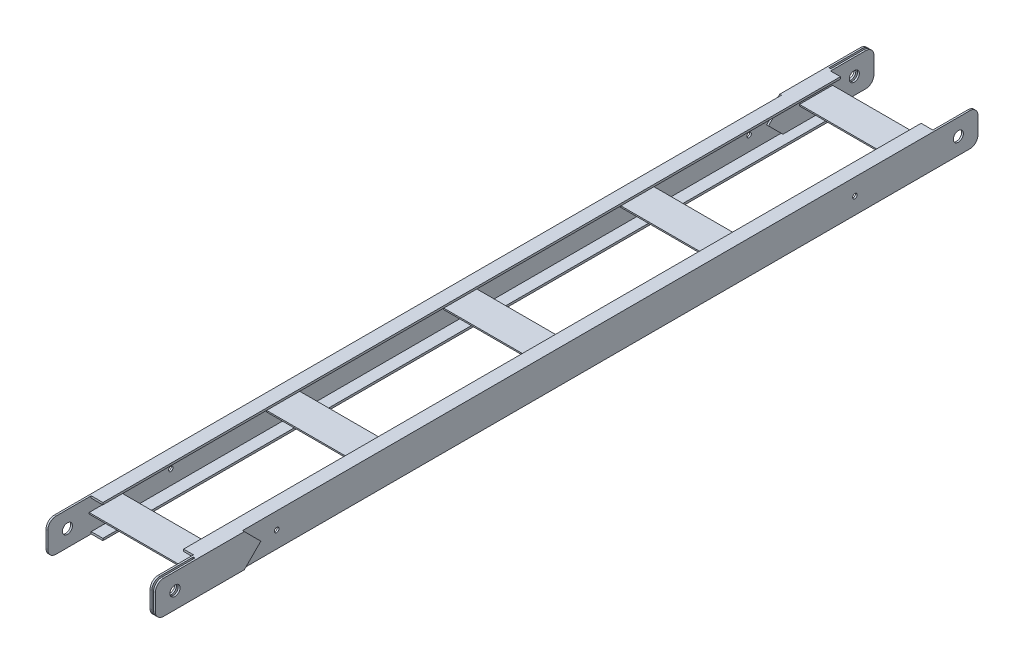
SolidWorks part; units mm, degrees
ref_plane "前视基准面" through (0, 0, 0) normal (0, 0, 1) x (1, 0, 0)
ref_plane "上视基准面" through (0, 0, 0) normal (0, 1, 0) x (1, 0, 0)
ref_plane "右视基准面" through (0, 0, 0) normal (1, 0, 0) x (0, 0, -1)
sketch "草图2" plane through (0, 0, 0) normal (0, 0, 1) x (1, 0, 0)
  line L0 (0, 0) -> (0, 160)
  line L1 (0, 160) -> (65, 160)
  line L2 (65, 160) -> (65, 150)
  line L3 (65, 150) -> (8.5, 150)
  line L4 (8.5, 150) -> (8.5, 10)
  line L5 (8.5, 10) -> (65, 10)
  line L6 (65, 10) -> (65, 0)
  line L7 (65, 0) -> (0, 0)
  line L8 (455, 160) -> (520, 160)
  line L9 (520, 160) -> (520, 0)
  line L10 (520, 0) -> (455, 0)
  line L11 (455, 0) -> (455, 10)
  line L12 (455, 10) -> (511.5, 10)
  line L13 (511.5, 10) -> (511.5, 150)
  line L14 (511.5, 150) -> (455, 150)
  line L15 (455, 150) -> (455, 160)
  dimension "D1" = 160
  dimension "D2" = 10
  dimension "D3" = 8.5
  dimension "D4" = 65
  dimension "D5" = 520
extrude "拉伸1" add sketch "草图2" along normal blind 3985
sketch "草图5" plane through (0, 0, 0) normal (-1, 0, 0) x (0, 0, 1)
  line L0 (200, 95) -> (360, 95)
  line L1 (360, 95) -> (360, 88.5)
  line L2 (283.25, 88.5) -> (360, 88.5)
  line L3 (283.25, 88.5) -> (283.25, 48.5)
  line L4 (283.25, 48.5) -> (276.75, 48.5)
  line L5 (276.75, 48.5) -> (276.75, 88.5)
  line L6 (276.75, 88.5) -> (200, 88.5)
  line L7 (200, 88.5) -> (200, 95)
  line L8 (0, 160) -> (0, 0) construction
  point P10 (0, 80)
  dimension "D1" = 160
  dimension "D2" = 6.5
  dimension "D3" = 6.5
  dimension "D4" = 40
  dimension "D5" = 200
  dimension "D6" = 15
extrude "拉伸3" add sketch "草图5" against normal blind 520
sketch "草图6" plane through (0, 160, 0) normal (0, 1, 0) x (1, 0, 0)
  line L0 (520, 0) -> (455, 0) construction
  line L1 (511.5, 0) -> (8.5, 0)
  line L2 (511.5, 0) -> (511.5, -200)
  line L3 (511.5, -200) -> (8.5, -200)
  line L4 (8.5, 0) -> (8.5, -200)
  line L5 (65, -3985) -> (0, -3985) construction
  line L6 (511.5, -3785) -> (8.5, -3785)
  line L7 (511.5, -3785) -> (511.5, -3985)
  line L8 (511.5, -3985) -> (8.5, -3985)
  line L9 (8.5, -3785) -> (8.5, -3985)
  line L10 (520, -3985) -> (520, 0) construction
  line L11 (0, -3985) -> (0, 0) construction
  dimension "D1" = 8.5
  dimension "D2" = 8.5
  dimension "D3" = 200
  dimension "D4" = 200
  dimension "D5" = 8.5
  dimension "D6" = 8.5
extrude "拉伸4" cut sketch "草图6" against normal through all
pattern_linear "阵列(线性)1" count 5 spacing 856.25 along (0, 0, 1) of "拉伸3"
sketch "草图19" plane through (520, 0, 0) normal (1, 0, 0) x (0, 0, -1)
  line L0 (-3985, 0) -> (0, 0) construction
  line L1 (-3985, 160) -> (-3555, 160)
  line L2 (-3985, 160) -> (-3985, 0)
  line L3 (-3985, 0) -> (-3555, 0)
  line L4 (-3555, 160) -> (-3475, 80)
  line L5 (-3475, 80) -> (-3555, 0)
  dimension "D1" = 430
extrude "拉伸11" add sketch "草图19" along normal blind 8.5
pattern_linear "阵列(线性)2" count 2 spacing 17 along (-1, 0, 0) of "拉伸11"
sketch "草图22" plane through (0, 160, 0) normal (0, 1, 0) x (1, 0, 0)
  line L0 (528.5, -3985) -> (503, -3985) construction
  line L1 (511.5, -3785) -> (520, -3785)
  line L2 (511.5, -3785) -> (511.5, -3985)
  line L3 (511.5, -3985) -> (520, -3985)
  line L4 (520, -3785) -> (520, -3985)
  line L5 (528.5, -3555) -> (528.5, -3985) construction
  line L6 (503, -3785) -> (503, -3985) construction
  line L7 (503, -3785) -> (455, -3785) construction
  dimension "D1" = 8.5
  dimension "D2" = 8.5
extrude "拉伸12" cut sketch "草图22" against normal through all
sketch "草图23" plane through (0, 0, 0) normal (-1, 0, 0) x (0, 0, 1)
  line L0 (0, 160) -> (0, 0) construction
  line L2 (3985, 0) -> (0, 0) construction
  line L3 (3985, 160) -> (3985, 0) construction
  line L4 (3985, 160) -> (0, 160) construction
  circle A0 centre (95, 80) radius 24.25
  circle A1 centre (3890, 80) radius 24.25
  dimension "D3" = 48.5
  dimension "D4" = 48.5
  dimension "D1" = 95
  dimension "D2" = 80
  dimension "D5" = 95
  dimension "D6" = 80
extrude "拉伸13" cut sketch "草图23" against normal through all
sketch "草图26" plane through (0, 0, 0) normal (-1, 0, 0) x (0, 0, 1)
  line L0 (0, 160) -> (0, 0)
  line L1 (0, 160) -> (430, 160)
  line L2 (430, 160) -> (510, 80)
  line L3 (510, 80) -> (430, 0)
  line L4 (0, 0) -> (430, 0)
  dimension "D1" = 430
extrude "拉伸14" add sketch "草图26" along normal blind 8.5
pattern_linear "阵列(线性)3" count 2 spacing 17 along (1, 0, 0) of "拉伸14"
sketch "草图27" plane through (0, 160, 0) normal (0, 1, 0) x (1, 0, 0)
  line L0 (17, 0) -> (-8.5, 0) construction
  line L1 (0, 0) -> (8.5, 0)
  line L2 (0, 0) -> (0, -200)
  line L3 (0, -200) -> (8.5, -200)
  line L4 (8.5, 0) -> (8.5, -200)
  line L5 (-8.5, -430) -> (-8.5, 0) construction
  line L6 (17, -200) -> (17, 0) construction
  line L7 (17, -200) -> (65, -200) construction
  dimension "D1" = 8.5
  dimension "D2" = 8.5
extrude "拉伸15" cut sketch "草图27" against normal through all
sketch "草图28" plane through (-8.5, 0, 0) normal (-1, 0, 0) x (0, 0, 1)
  line L0 (0, 160) -> (0, 0) construction
  line L1 (430, 160) -> (0, 160) construction
  circle A0 centre (95, 80) radius 24.25
  dimension "D1" = 48.5
  dimension "D2" = 95
  dimension "D3" = 80
extrude "拉伸16" cut sketch "草图28" against normal through all
fillet "圆角2" radius 40 10 edges at (4.25, 160, 3985) (4.25, 0, 3985) (524.25, 0, 3985) (507.25, 0, 3985) (524.25, 160, 3985) (507.25, 160, 3985) (12.75, 160, 0) (12.75, 0, 0) (515.75, 160, 0) (515.75, 0, 0)
sketch "草图29" plane through (0, 0, 3785) normal (0, 0, 1) x (1, 0, 0)
  line L1 (8.5, 160) -> (503, 160)
  line L2 (8.5, 160) -> (8.5, 150)
  line L3 (8.5, 150) -> (503, 150)
  line L4 (503, 160) -> (503, 150)
  line L5 (503, 0) -> (8.5, 0)
  line L6 (503, 0) -> (503, 10)
  line L7 (503, 10) -> (8.5, 10)
  line L8 (8.5, 0) -> (8.5, 10)
extrude "拉伸17" cut sketch "草图29" against normal blind 10
sketch "草图30" plane through (0, 0, 200) normal (0, 0, -1) x (-1, 0, 0)
  line L1 (-17, 160) -> (-511.5, 160)
  line L2 (-17, 160) -> (-17, 150)
  line L3 (-17, 150) -> (-511.5, 150)
  line L4 (-511.5, 160) -> (-511.5, 150)
  line L5 (-511.5, 10) -> (-17, 10)
  line L6 (-511.5, 10) -> (-511.5, 0)
  line L7 (-511.5, 0) -> (-17, 0)
  line L8 (-17, 10) -> (-17, 0)
extrude "拉伸18" cut sketch "草图30" against normal blind 10
sketch "草图31" plane through (520, 0, 0) normal (1, 0, 0) x (0, 0, -1)
  line L0 (-95, 80) -> (-3890, 80) construction
  circle A0 centre (-595, 80) radius 11
  circle A1 centre (-3390, 80) radius 11
  dimension "D1" = 22
  dimension "D2" = 22
  dimension "D3" = 500
  dimension "D4" = 500
extrude "拉伸19" cut sketch "草图31" against normal through all
